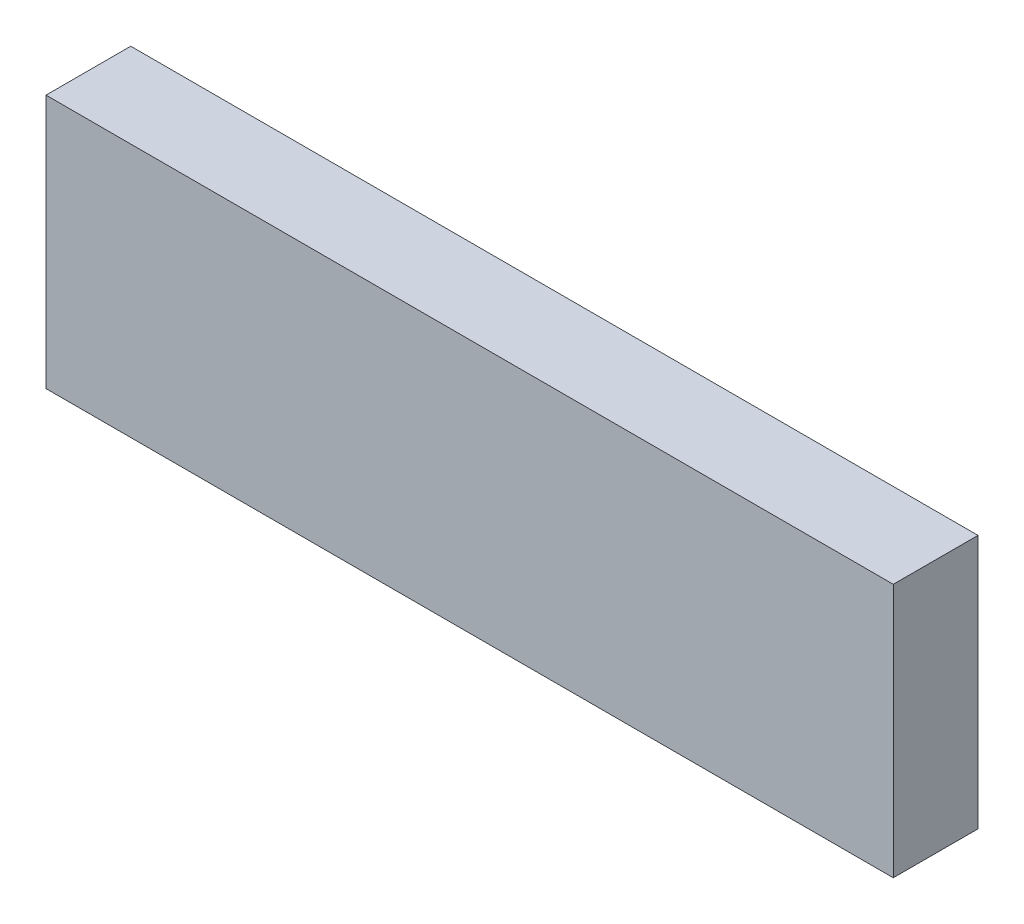
SolidWorks part; units mm, degrees
ref_plane "Front Plane" through (0, 0, 0) normal (0, 0, 1) x (1, 0, 0)
ref_plane "Top Plane" through (0, 0, 0) normal (0, 1, 0) x (1, 0, 0)
ref_plane "Right Plane" through (0, 0, 0) normal (1, 0, 0) x (0, 0, -1)
sketch "Sketch1" plane through (0, 0, 0) normal (0, 0, 1) x (1, 0, 0)
  line L1 (0, 0) -> (200, 0)
  line L2 (0, 0) -> (0, 60)
  line L3 (0, 60) -> (200, 60)
  line L4 (200, 0) -> (200, 60)
  dimension "D1" = 200
  dimension "D2" = 60
extrude "Boss-Extrude1" add sketch "Sketch1" along normal blind 20
